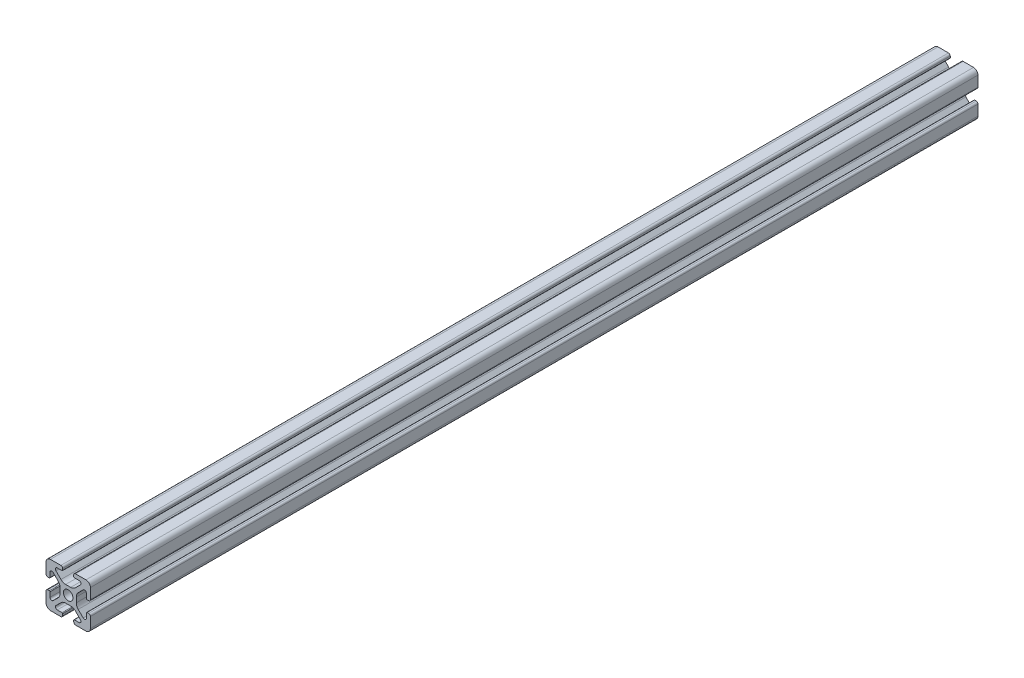
SolidWorks part; units mm, degrees
material "Alliage 1060"
ref_plane "Plan de face" through (0, 0, 0) normal (0, 0, 1) x (1, 0, 0)
ref_plane "Plan de dessus" through (0, 0, 0) normal (0, 1, 0) x (1, 0, 0)
ref_plane "Plan de droite" through (0, 0, 0) normal (1, 0, 0) x (0, 0, -1)
sketch "Esquisse1" plane through (0, 0, 0) normal (0, 0, 1) x (1, 0, 0)
  line L108 (-3.2559, 4.5287) -> (-5.5062, 6.779)
  line L109 (-4.9176, 8.2) -> (-2.8, 8.2)
  line L110 (-2.5, 8.5) -> (-2.5, 9.2)
  line L111 (-3.3, 10) -> (-8, 10)
  line L112 (-10, 8) -> (-10, 3.3)
  line L113 (-9.2, 2.5) -> (-8.5, 2.5)
  line L114 (-8.2, 2.8) -> (-8.2, 4.9176)
  line L115 (-6.779, 5.5062) -> (-4.5287, 3.2559)
  line L116 (-3.65, 1.1346) -> (-3.65, -1.1346)
  line L117 (-4.5287, -3.2559) -> (-6.779, -5.5062)
  line L118 (-8.2, -4.9176) -> (-8.2, -2.8)
  line L119 (-8.5, -2.5) -> (-9.2, -2.5)
  line L120 (-10, -3.3) -> (-10, -8)
  line L121 (-8, -10) -> (-3.3, -10)
  line L122 (-2.5, -9.2) -> (-2.5, -8.5)
  line L123 (-2.8, -8.2) -> (-4.9176, -8.2)
  line L124 (-5.5062, -6.779) -> (-3.2559, -4.5287)
  line L125 (-1.1346, -3.65) -> (1.1346, -3.65)
  line L126 (3.2559, -4.5287) -> (5.5062, -6.779)
  line L127 (4.9176, -8.2) -> (2.8, -8.2)
  line L128 (2.5, -8.5) -> (2.5, -9.2)
  line L129 (3.3, -10) -> (8, -10)
  line L130 (10, -8) -> (10, -3.3)
  line L131 (9.2, -2.5) -> (8.5, -2.5)
  line L132 (8.2, -2.8) -> (8.2, -4.9176)
  line L133 (6.779, -5.5062) -> (4.5287, -3.2559)
  line L134 (3.65, -1.1346) -> (3.65, 1.1346)
  line L135 (4.5287, 3.2559) -> (6.779, 5.5062)
  line L136 (8.2, 4.9176) -> (8.2, 2.8)
  line L137 (8.5, 2.5) -> (9.2, 2.5)
  line L138 (10, 3.3) -> (10, 8)
  line L139 (8, 10) -> (3.3, 10)
  line L140 (2.5, 9.2) -> (2.5, 8.5)
  line L141 (2.8, 8.2) -> (4.9176, 8.2)
  line L142 (5.5062, 6.779) -> (3.2559, 4.5287)
  line L143 (1.1346, 3.65) -> (-1.1346, 3.65)
  arc A42 (-2.15, 0) -> (2.15, 0) centre (0, 0) ccw
  arc A43 (2.15, 0) -> (-2.15, 0) centre (0, 0) ccw
  arc A108 (-4.9176, 8.2) -> (-5.5062, 6.779) centre (-4.9176, 7.3676) ccw
  arc A109 (-2.8, 8.2) -> (-2.5, 8.5) centre (-2.8, 8.5) ccw
  arc A110 (-2.5, 9.2) -> (-3.3, 10) centre (-3.3, 9.2) ccw
  arc A111 (-8, 10) -> (-10, 8) centre (-8, 8) ccw
  arc A112 (-10, 3.3) -> (-9.2, 2.5) centre (-9.2, 3.3) ccw
  arc A113 (-8.5, 2.5) -> (-8.2, 2.8) centre (-8.5, 2.8) ccw
  arc A114 (-6.779, 5.5062) -> (-8.2, 4.9176) centre (-7.3676, 4.9176) ccw
  arc A115 (-3.65, 1.1346) -> (-4.5287, 3.2559) centre (-6.65, 1.1346) ccw
  arc A116 (-4.5287, -3.2559) -> (-3.65, -1.1346) centre (-6.65, -1.1346) ccw
  arc A117 (-8.2, -4.9176) -> (-6.779, -5.5062) centre (-7.3676, -4.9176) ccw
  arc A118 (-8.2, -2.8) -> (-8.5, -2.5) centre (-8.5, -2.8) ccw
  arc A119 (-9.2, -2.5) -> (-10, -3.3) centre (-9.2, -3.3) ccw
  arc A120 (-10, -8) -> (-8, -10) centre (-8, -8) ccw
  arc A121 (-3.3, -10) -> (-2.5, -9.2) centre (-3.3, -9.2) ccw
  arc A122 (-2.5, -8.5) -> (-2.8, -8.2) centre (-2.8, -8.5) ccw
  arc A123 (-5.5062, -6.779) -> (-4.9176, -8.2) centre (-4.9176, -7.3676) ccw
  arc A124 (-1.1346, -3.65) -> (-3.2559, -4.5287) centre (-1.1346, -6.65) ccw
  arc A125 (3.2559, -4.5287) -> (1.1346, -3.65) centre (1.1346, -6.65) ccw
  arc A126 (4.9176, -8.2) -> (5.5062, -6.779) centre (4.9176, -7.3676) ccw
  arc A127 (2.8, -8.2) -> (2.5, -8.5) centre (2.8, -8.5) ccw
  arc A128 (2.5, -9.2) -> (3.3, -10) centre (3.3, -9.2) ccw
  arc A129 (8, -10) -> (10, -8) centre (8, -8) ccw
  arc A130 (10, -3.3) -> (9.2, -2.5) centre (9.2, -3.3) ccw
  arc A131 (8.5, -2.5) -> (8.2, -2.8) centre (8.5, -2.8) ccw
  arc A132 (6.779, -5.5062) -> (8.2, -4.9176) centre (7.3676, -4.9176) ccw
  arc A133 (3.65, -1.1346) -> (4.5287, -3.2559) centre (6.65, -1.1346) ccw
  arc A134 (4.5287, 3.2559) -> (3.65, 1.1346) centre (6.65, 1.1346) ccw
  arc A135 (8.2, 4.9176) -> (6.779, 5.5062) centre (7.3676, 4.9176) ccw
  arc A136 (8.2, 2.8) -> (8.5, 2.5) centre (8.5, 2.8) ccw
  arc A137 (9.2, 2.5) -> (10, 3.3) centre (9.2, 3.3) ccw
  arc A138 (10, 8) -> (8, 10) centre (8, 8) ccw
  arc A139 (3.3, 10) -> (2.5, 9.2) centre (3.3, 9.2) ccw
  arc A140 (2.5, 8.5) -> (2.8, 8.2) centre (2.8, 8.5) ccw
  arc A141 (5.5062, 6.779) -> (4.9176, 8.2) centre (4.9176, 7.3676) ccw
  arc A142 (1.1346, 3.65) -> (3.2559, 4.5287) centre (1.1346, 6.65) ccw
  arc A143 (-3.2559, 4.5287) -> (-1.1346, 3.65) centre (-1.1346, 6.65) ccw
extrude "Boss.-Extru.1" add sketch "Esquisse1" along normal blind 400
